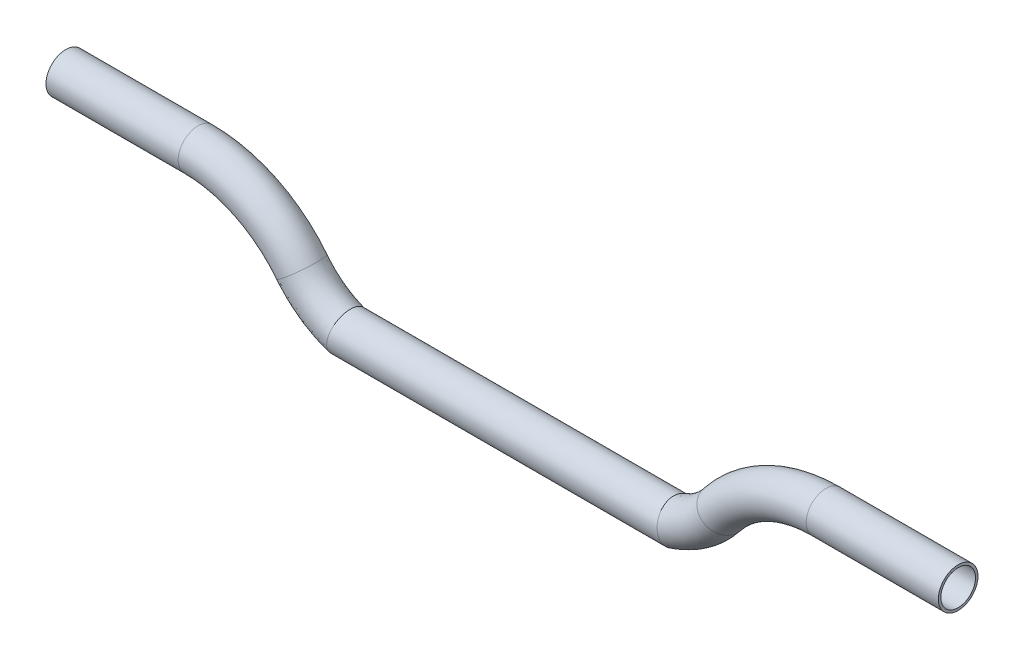
SolidWorks part; units mm, degrees
material "不锈钢 (铁素体)"
ref_plane "前视" through (0, 0, 0) normal (0, 0, 1) x (1, 0, 0)
ref_plane "上视" through (0, 0, 0) normal (0, 1, 0) x (1, 0, 0)
ref_plane "右视" through (0, 0, 0) normal (1, 0, 0) x (0, 0, -1)
sketch "草图1" plane through (0, 0, 0) normal (0, 0, 1) x (1, 0, 0)
  line L0 (-270.0268, 50) -> (-190.0268, 50)
  line L1 (-100, 0) -> (100, 0)
  line L2 (0, 93.0174) -> (0, -86.7232) construction
  line L3 (270.0268, 50) -> (190.0268, 50)
  arc A0 (-190.0268, 50) -> (-127.1543, 19.4677) centre (-190.0268, -30) cw
  arc A1 (-127.1543, 19.4677) -> (-100, 0) centre (-80, 56.5685) ccw
  arc A2 (127.1543, 19.4677) -> (100, 0) centre (80, 56.5685) cw
  arc A3 (190.0268, 50) -> (127.1543, 19.4677) centre (190.0268, -30) ccw
  point P12 (0, 0)
  dimension "D2" = 80
  dimension "D3" = 60
  dimension "D1" = 80
  dimension "D4" = 100
  dimension "D5" = 20
  dimension "D6" = 30
ref_plane "基准面1" through (-270.0268, 0, 0) normal (1, 0, 0) x (0, 0, -1)
sketch "草图2" plane through (-270.0268, 0, 0) normal (1, 0, 0) x (0, 0, -1)
  circle A0 centre (0, 50) radius 10.5
  circle A1 centre (0, 50) radius 12
  dimension "D1" = 24
  dimension "D2" = 1.5
sweep "扫描1" add profiles "草图2" path "草图1"
